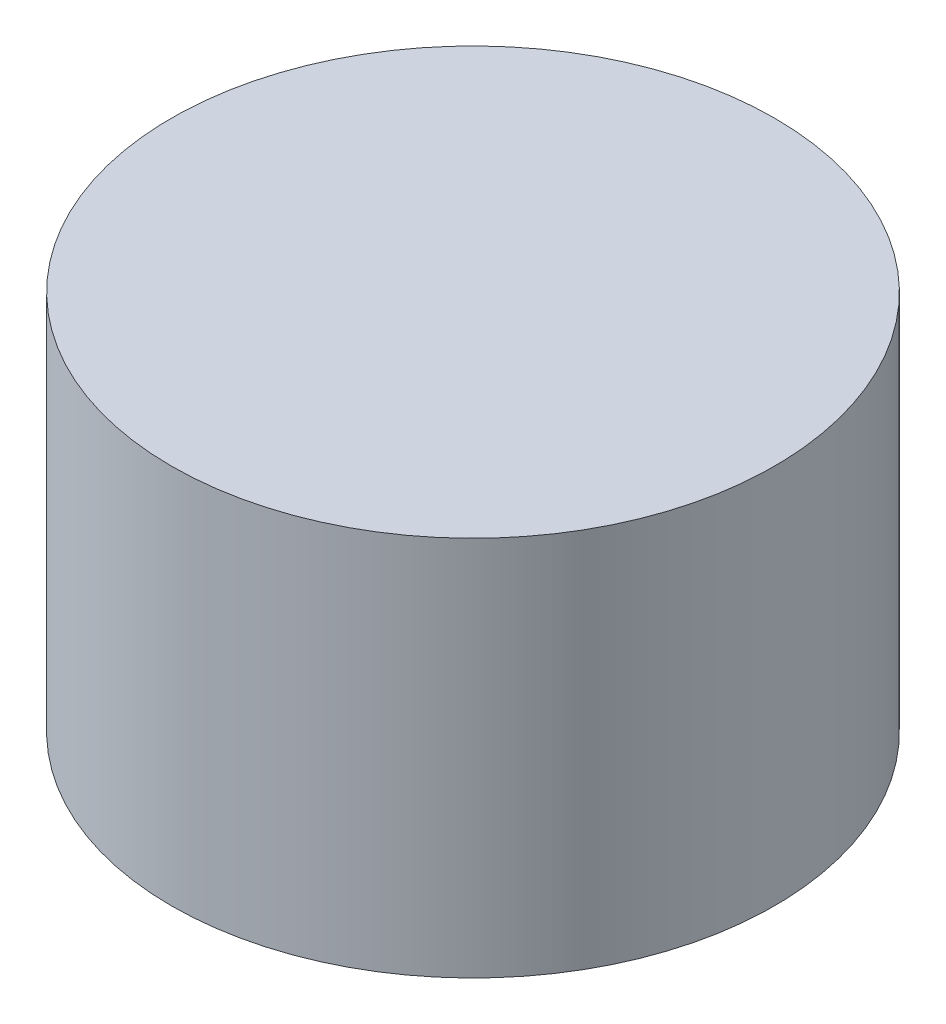
SolidWorks part; units mm, degrees
ref_plane "Front Plane" through (0, 0, 0) normal (0, 0, 1) x (1, 0, 0)
ref_plane "Top Plane" through (0, 0, 0) normal (0, 1, 0) x (1, 0, 0)
ref_plane "Right Plane" through (0, 0, 0) normal (1, 0, 0) x (0, 0, -1)
sketch "Sketch1" plane through (0, 0, 0) normal (0, 1, 0) x (1, 0, 0)
  circle A0 centre (0, 0) radius 20.9
extrude "Boss-Extrude1" add sketch "Sketch1" against normal blind 26.4 contours A0
